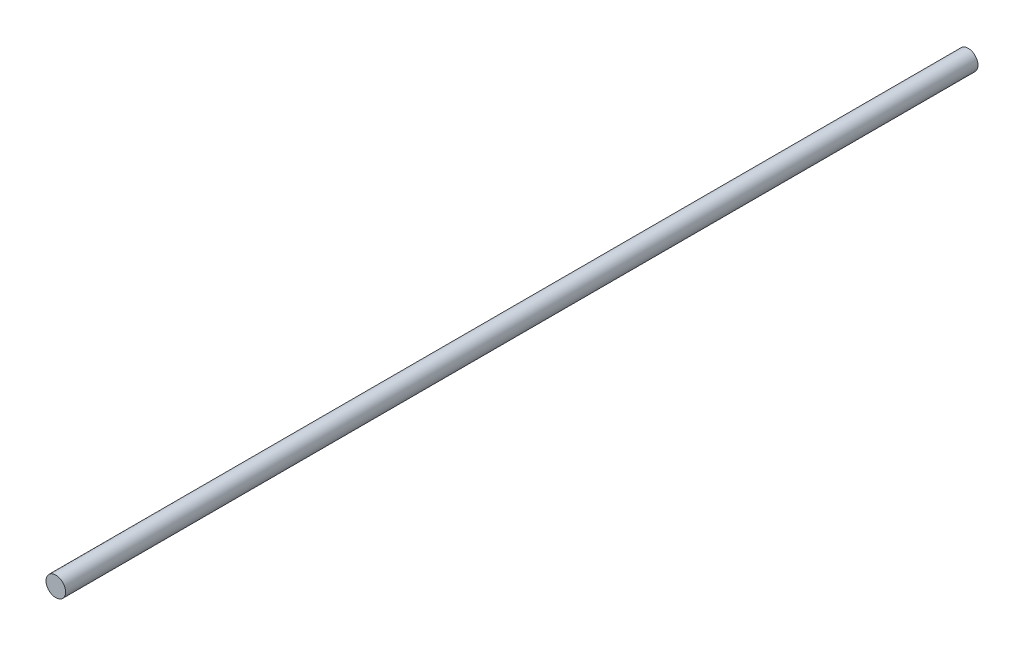
SolidWorks part; units mm, degrees
material "6061 Alloy"
ref_plane "Front Plane" through (0, 0, 0) normal (0, 0, 1) x (1, 0, 0)
ref_plane "Top Plane" through (0, 0, 0) normal (0, 1, 0) x (1, 0, 0)
ref_plane "Right Plane" through (0, 0, 0) normal (1, 0, 0) x (0, 0, -1)
sketch "Sketch1" plane through (0, 0, 0) normal (0, 0, 1) x (1, 0, 0)
  circle A0 centre (0, 0) radius 6.35
  dimension "D1" = 12.7
extrude "Boss-Extrude1" add sketch "Sketch1" along normal mid plane 590.55
